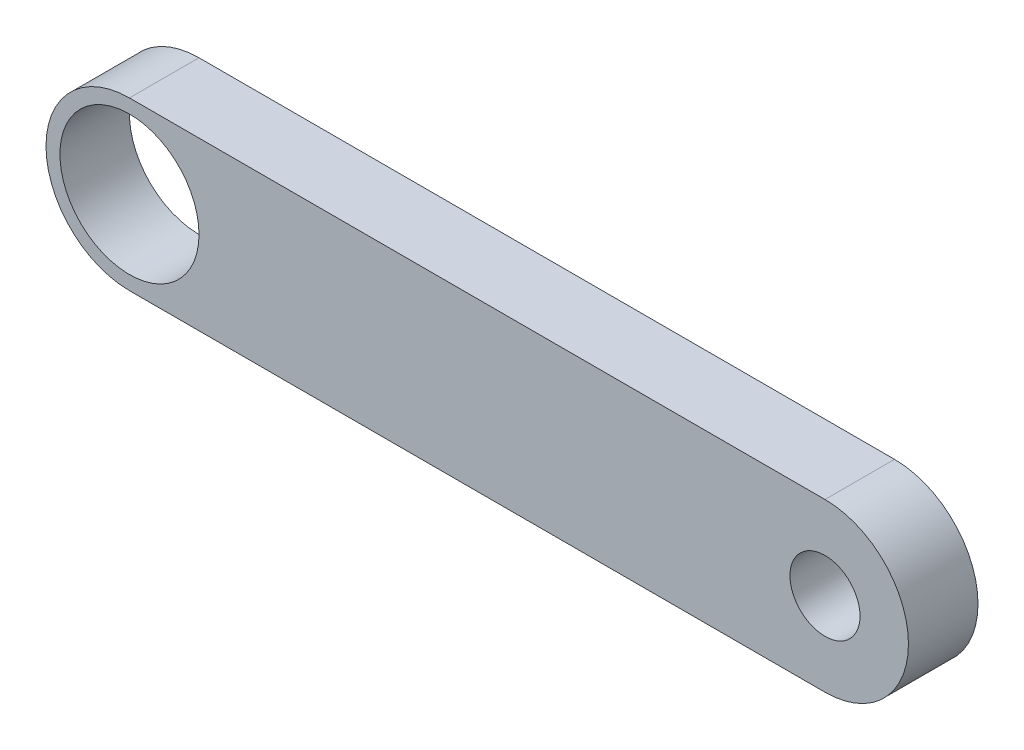
SolidWorks part; units mm, degrees
ref_plane "前视基准面" through (0, 0, 0) normal (0, 0, 1) x (1, 0, 0)
ref_plane "上视基准面" through (0, 0, 0) normal (0, 1, 0) x (1, 0, 0)
ref_plane "右视基准面" through (0, 0, 0) normal (1, 0, 0) x (0, 0, -1)
other "Configuration Table"
sketch "草图1" plane through (0, 0, 0) normal (0, 0, 1) x (1, 0, 0)
  line L0 (0, 0) -> (50, 0) construction
  line L1 (0, 6) -> (50, 6)
  line L2 (0, -6) -> (50, -6)
  arc A0 (0, 6) -> (0, -6) centre (0, 0) ccw
  arc A1 (50, -6) -> (50, 6) centre (50, 0) ccw
  circle A3 centre (50, 0) radius 2.519
  point P3 (25, 0)
  dimension "D2" = 6
  dimension "D3" = 5.0379
  dimension "D1" = 50
extrude "凸台-拉伸1" add sketch "草图1" along normal blind 5
sketch "草图2" plane through (0, 0, 5) normal (0, 0, 1) x (1, 0, 0)
  circle A0 centre (0, 0) radius 5
extrude "切除-拉伸1" cut sketch "草图2" against normal blind 5
